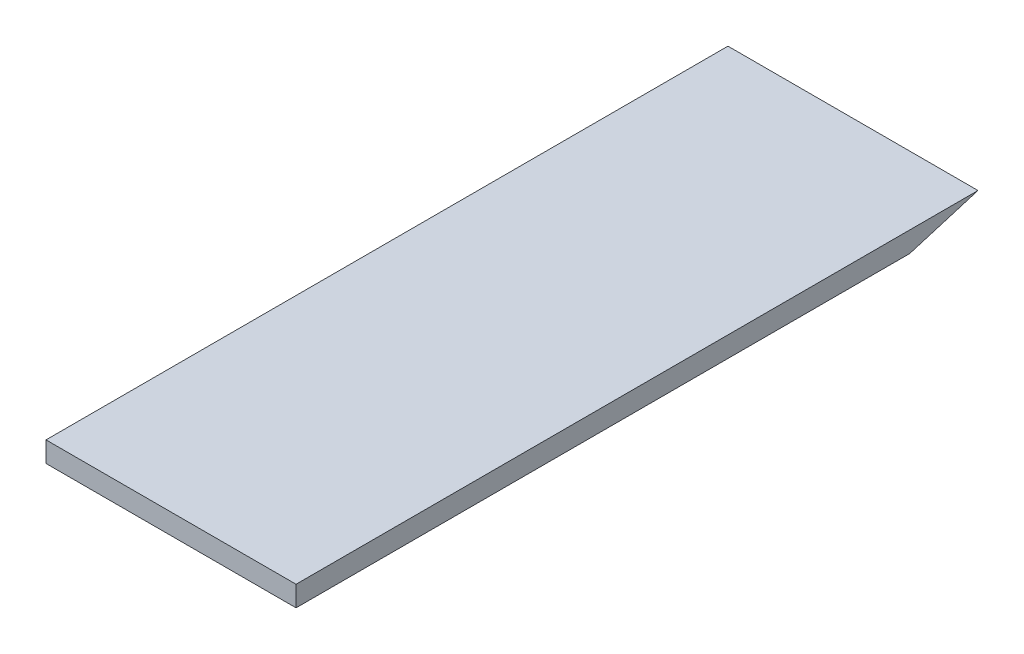
SolidWorks part; units mm, degrees
ref_plane "Front Plane" through (0, 0, 0) normal (0, 0, 1) x (1, 0, 0)
ref_plane "Top Plane" through (0, 0, 0) normal (0, 1, 0) x (1, 0, 0)
ref_plane "Right Plane" through (0, 0, 0) normal (1, 0, 0) x (0, 0, -1)
sketch "Sketch1" plane through (0, 0, 0) normal (1, 0, 0) x (0, 0, -1)
  line L19 (0, 9) -> (0, 0)
  line L20 (0, 0) -> (270, 0)
  line L21 (270, 0) -> (300, 9)
  line L37 (0, 9) -> (300, 9)
  point P13 (0, 0)
  point P23 (0, 0)
  dimension "D1" = 9
  dimension "D8" = 30
  dimension "D9" = 270
extrude "Boss-Extrude1" add sketch "Sketch1" along normal blind 110 contours L19 L20 L21 L37
